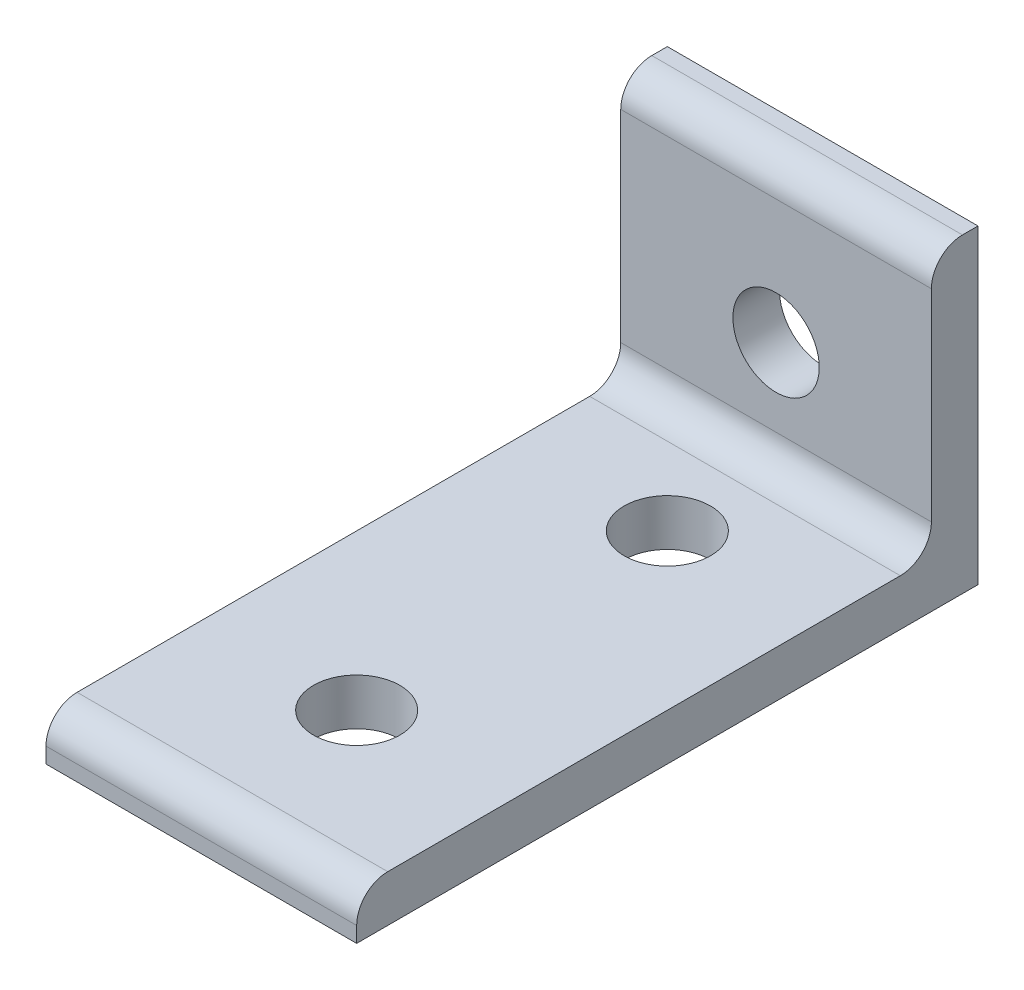
SolidWorks part; units mm, degrees
material "6061-T6 (SS)"
ref_plane "Front Plane" through (0, 0, 0) normal (0, 0, 1) x (1, 0, 0)
ref_plane "Top Plane" through (0, 0, 0) normal (0, 1, 0) x (1, 0, 0)
ref_plane "Right Plane" through (0, 0, 0) normal (1, 0, 0) x (0, 0, -1)
sketch "Sketch1" plane through (0, 0, 0) normal (1, 0, 0) x (0, 0, -1)
  line L0 (-20, -10) -> (20, -10)
  line L1 (20, -10) -> (20, 10)
  line L2 (20, 10) -> (19, 10)
  line L3 (17, 8) -> (17, -5)
  line L4 (15, -7) -> (-18, -7)
  line L5 (-20, -9) -> (-20, -10)
  line L6 (-20, -10) -> (20, 10) construction
  arc A0 (19, 10) -> (17, 8) centre (19, 8) ccw
  arc A1 (17, -5) -> (15, -7) centre (15, -5) cw
  arc A2 (-18, -7) -> (-20, -9) centre (-18, -9) ccw
  point P9 (17, 10)
  dimension "D4" = 2
  dimension "D1" = 40
  dimension "D2" = 20
  dimension "D3" = 3
extrude "Boss-Extrude1" add sketch "Sketch1" along normal mid plane 20
sketch "Sketch2" plane through (0, 0, -20) normal (0, 0, -1) x (-1, 0, 0)
  circle A0 centre (0, 0) radius 2.78
  dimension "D1" = 5.56
extrude "Cut-Extrude1" cut sketch "Sketch2" against normal through all both and the other way through all
sketch "Sketch3" plane through (0, -10, 0) normal (0, -1, 0) x (1, 0, 0)
  line L0 (10, 20) -> (-10, 0) construction
  line L1 (-10, 20) -> (-10, -20) construction
  line L2 (-10, 0) -> (10, -20) construction
  circle A0 centre (0, 10) radius 2.78
  circle A1 centre (0, -10) radius 2.78
  dimension "D1" = 5.56
extrude "Cut-Extrude2" cut sketch "Sketch3" against normal through all both and the other way through all
